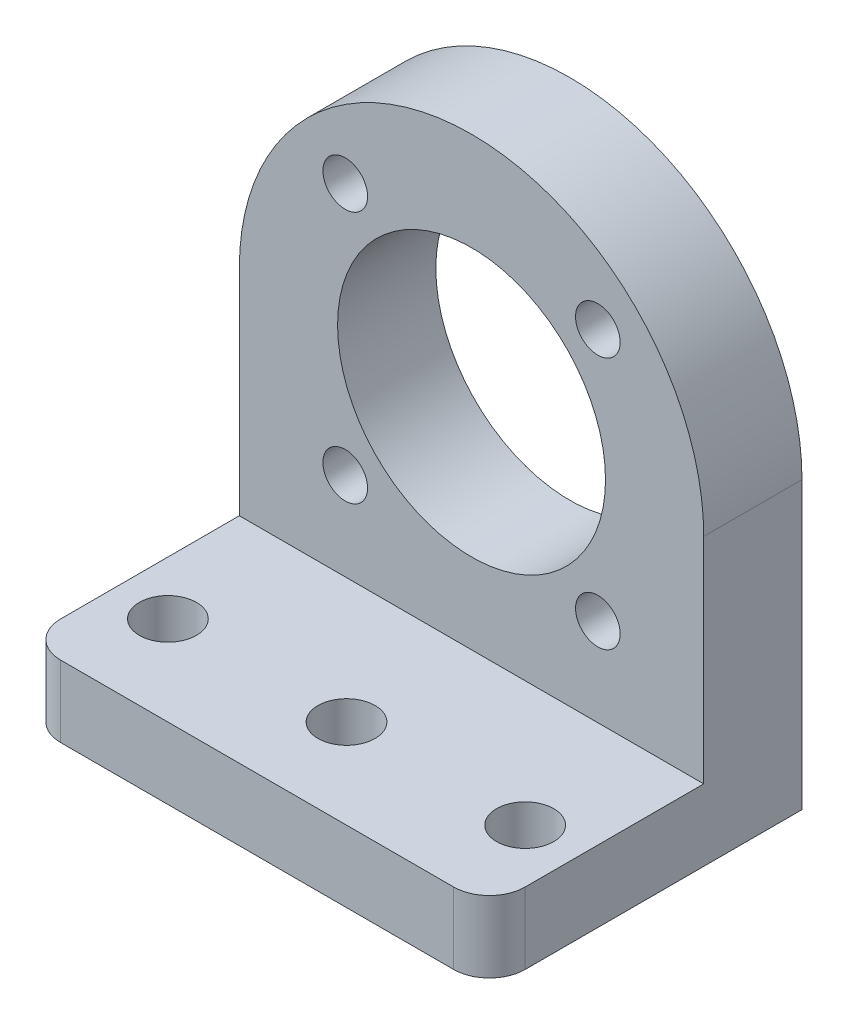
SolidWorks part; units mm, degrees
material "6061 合金"
ref_plane "前视基准面" through (0, 0, 0) normal (0, 0, 1) x (1, 0, 0)
ref_plane "上视基准面" through (0, 0, 0) normal (0, 1, 0) x (1, 0, 0)
ref_plane "右视基准面" through (0, 0, 0) normal (1, 0, 0) x (0, 0, -1)
other "Configuration Table"
sketch "草图1" plane through (0, 0, 0) normal (0, 0, 1) x (1, 0, 0)
  line L0 (-7.0711, 7.0711) -> (0, 0) construction
  line L1 (0, 0) -> (-7.5, 0) construction
  line L2 (-13, 0) -> (-13, -16)
  line L3 (-13, -16) -> (13, -16)
  line L4 (13, -16) -> (13, 0)
  circle A0 centre (0, 0) radius 7.5
  arc A1 (13, 0) -> (-13, 0) centre (0, 0) ccw
  circle A2 centre (-7.0711, 7.0711) radius 1.25
  circle A3 centre (7.0711, 7.0711) radius 1.25
  circle A4 centre (7.0711, -7.0711) radius 1.25
  circle A5 centre (-7.0711, -7.0711) radius 1.25
  point P9 (0, 0)
  point P12 (7.9665, 4.5574)
  point P13 (0, 0)
  point P20 (0, 0)
  dimension "D1" = 15
  dimension "D2" = 26
  dimension "D3" = 2.5
  dimension "D4" = 10
  dimension "D5" = 45
  dimension "D7" = 16
  dimension "D6" = 4
extrude "凸台-拉伸1" add sketch "草图1" along normal blind 5.5
cosmetic thread "装饰螺纹线1" parameters "D2"=3
cosmetic thread "装饰螺纹线2" parameters "D2"=3
cosmetic thread "装饰螺纹线3" parameters "D2"=3
cosmetic thread "装饰螺纹线4" parameters "D2"=3
sketch "草图2" plane through (0, 0, 5.5) normal (0, 0, 1) x (1, 0, 0)
  line L0 (-13, 0) -> (-13, -16) construction
  line L1 (-13, -12) -> (13, -12)
  line L2 (-13, -12) -> (-13, -16)
  line L3 (-13, -16) -> (13, -16)
  line L4 (13, -12) -> (13, -16)
  dimension "D1" = 4
extrude "凸台-拉伸2" add sketch "草图2" along normal blind 12
sketch "草图3" plane through (0, -12, 0) normal (0, 1, 0) x (1, 0, 0)
  line L0 (-13, -17.5) -> (-13, -5.5) construction
  line L1 (13, -17.5) -> (-13, -17.5) construction
  line L2 (-10, -12.5) -> (0, -12.5) construction
  circle A0 centre (-10, -12.5) radius 1.6
  circle A1 centre (0, -12.5) radius 1.6
  circle A2 centre (10, -12.5) radius 1.6
  dimension "D1" = 3.2
  dimension "D2" = 3
  dimension "D3" = 5
  dimension "D5" = 10
  dimension "D4" = 3
extrude "切除-拉伸1" cut sketch "草图3" against normal blind 12
fillet "圆角1" radius 2 2 edges at (13, -14, 17.5) (-13, -14, 17.5)
